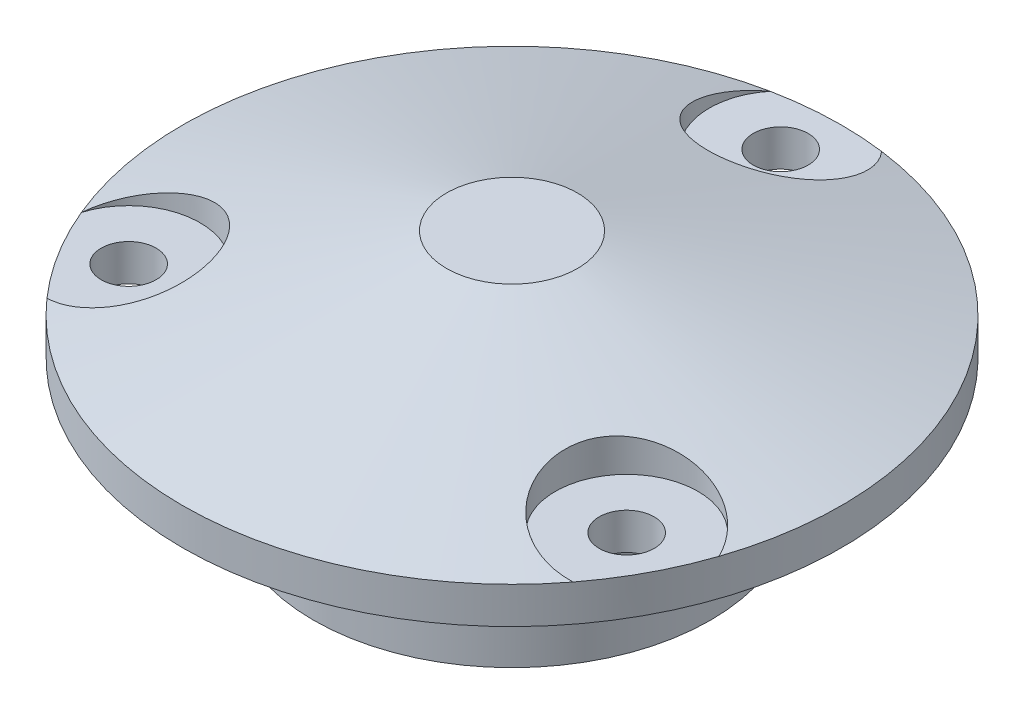
SolidWorks part; units mm, degrees
ref_plane "Plan de face" through (0, 0, 0) normal (0, 0, 1) x (1, 0, 0)
ref_plane "Plan de dessus" through (0, 0, 0) normal (0, 1, 0) x (1, 0, 0)
ref_plane "Plan de droite" through (0, 0, 0) normal (1, 0, 0) x (0, 0, -1)
sketch "Esquisse1" plane through (0, 0, 0) normal (0, 1, 0) x (1, 0, 0)
  circle A0 centre (0, 0) radius 9
  circle A1 centre (0, 0) radius 10.85
  dimension "D1" = 21.7
  dimension "D2" = 18
extrude "Boss.-Extru.1" add sketch "Esquisse1" along normal blind 7
sketch "Esquisse2" plane through (0, 7, 0) normal (0, 1, 0) x (1, 0, 0)
  circle A0 centre (0, 0) radius 18
  dimension "D1" = 36
extrude "Boss.-Extru.2" add sketch "Esquisse2" along normal blind 2
ref_plane "Plan1" through (0, 13, 0) normal (0, 1, 0) x (1, 0, 0)
sketch "Esquisse4" plane through (0, 9, 0) normal (0, 1, 0) x (1, 0, 0)
  circle A0 centre (0, 0) radius 18
extrude "Boss.-Extru.3" add sketch "Esquisse4" along normal blind 4 draft 74.5
sketch "Esquisse5" plane through (0, 7, 0) normal (0, -1, 0) x (1, 0, 0)
  circle A0 centre (-12.8987, 8.0413) radius 1.5
  circle A1 centre (0, 0) radius 18 construction
  circle A2 centre (13.4133, 7.15) radius 1.5
  circle A3 centre (-0.5146, -15.1913) radius 1.5
  point P10 (0, 0)
  dimension "D1" = 3
  dimension "D2" = 15.2
  dimension "D3" = 3
extrude "Enlèv. mat.-Extru.1" cut sketch "Esquisse5" against normal blind 4
sketch "Esquisse6" plane through (0, 13, 0) normal (0, 1, 0) x (1, 0, 0)
  circle A0 centre (-0.5146, 15.1913) radius 3.9
  circle A1 centre (13.4133, -7.15) radius 3.9
  circle A2 centre (-12.8987, -8.0413) radius 3.9
  point P10 (0, 0)
  dimension "D1" = 7.8
  dimension "D2" = 3
extrude "Enlèv. mat.-Extru.2" cut sketch "Esquisse6" against normal blind 4
